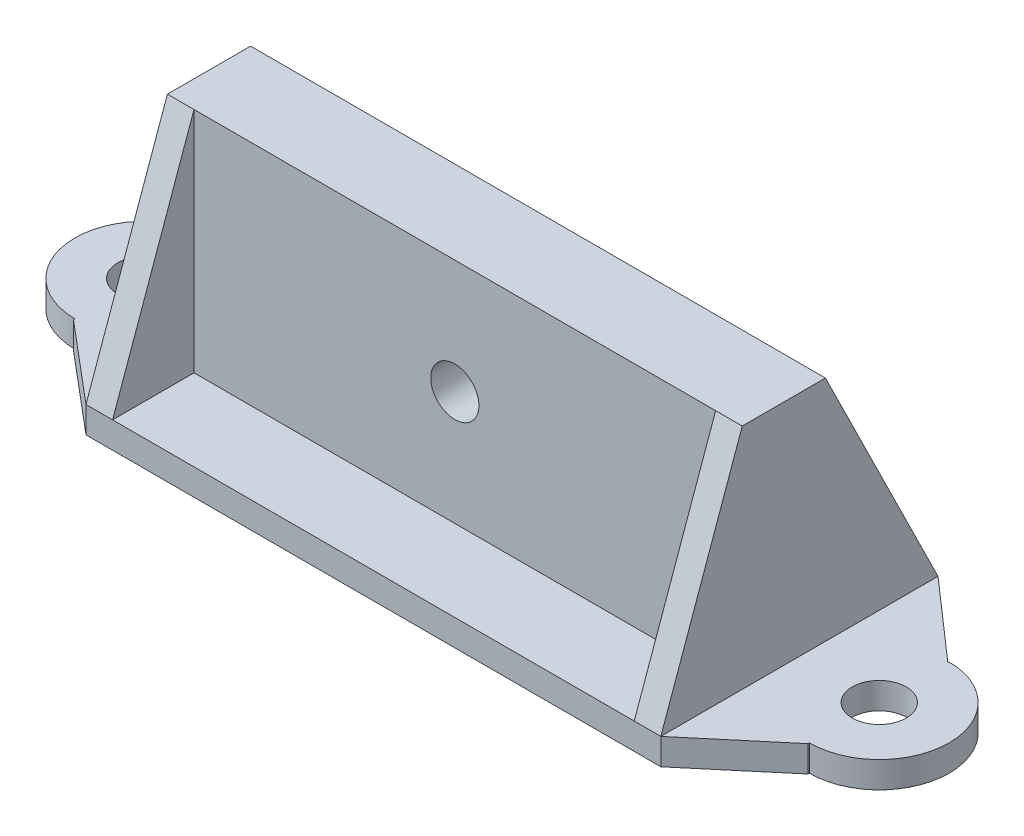
SolidWorks part; units mm, degrees
ref_plane "Alzado" through (0, 0, 0) normal (0, 0, 1) x (1, 0, 0)
ref_plane "Planta" through (0, 0, 0) normal (0, 1, 0) x (1, 0, 0)
ref_plane "Vista lateral" through (0, 0, 0) normal (1, 0, 0) x (0, 0, -1)
sketch "Croquis3" plane through (0, 0, 0) normal (0, 0, 1) x (1, 0, 0)
  line L1 (-37.635, -16.455) -> (37.635, -16.455)
  line L2 (-37.635, -16.455) -> (-37.635, 16.455)
  line L3 (-37.635, 16.455) -> (37.635, 16.455)
  line L4 (37.635, -16.455) -> (37.635, 16.455)
  line L5 (-37.635, -16.455) -> (37.635, 16.455) construction
  line L6 (-37.635, 16.455) -> (37.635, -16.455) construction
  point P0 (0, 0)
  dimension "D1" = 75.27
  dimension "D2" = 32.91
extrude "Saliente-Extruir1" add sketch "Croquis3" along normal blind 3.82
sketch "Croquis4" plane through (37.635, 0, 0) normal (1, 0, 0) x (0, 0, -1)
  line L0 (-3.82, -16.455) -> (0, -16.455)
  line L1 (0, -16.455) -> (0, 16.455)
  line L2 (-3.82, 16.455) -> (0, 16.455) construction
  line L3 (0, -16.455) -> (0, 16.455) construction
  line L4 (0, 16.455) -> (-3.82, 16.455)
  line L5 (-3.82, 16.455) -> (-15.57, -16.455)
  line L6 (-15.57, -16.455) -> (-3.82, -16.455)
  dimension "D1" = 11.75
extrude "Saliente-Extruir2" add sketch "Croquis4" along normal blind 3.84
sketch "Croquis5" plane through (-37.635, 0, 0) normal (-1, 0, 0) x (0, 0, 1)
  line L0 (3.82, -16.455) -> (0, -16.455)
  line L1 (0, -16.455) -> (0, 16.455)
  line L2 (0, 16.455) -> (3.82, 16.455)
  line L3 (3.82, 16.455) -> (15.57, -16.455)
  line L4 (15.57, -16.455) -> (3.82, -16.455)
extrude "Saliente-Extruir3" add sketch "Croquis5" along normal blind 3.84
sketch "Croquis8" plane through (0, -16.455, 0) normal (0, -1, 0) x (-1, 0, 0)
  line L0 (41.475, -15.57) -> (-41.475, -15.57)
  line L1 (-41.475, -15.57) -> (-41.475, 0)
  line L2 (-41.475, 0) -> (41.475, 0)
  line L3 (41.475, 0) -> (41.475, -15.57)
extrude "Saliente-Extruir5" add sketch "Croquis8" along normal blind 3.8
sketch "Croquis9" plane through (0, -20.255, 0) normal (0, -1, 0) x (1, 0, 0)
  line L0 (-41.475, 0) -> (-41.475, -24.43)
  line L5 (41.475, 0) -> (41.475, -24.43)
  line L6 (41.475, -24.43) -> (-41.475, -24.43)
  line L7 (41.475, 15.57) -> (-41.475, 15.57) construction
  line L8 (-41.475, 0) -> (41.475, 0)
  dimension "D1" = 40
extrude "Saliente-Extruir7" add sketch "Croquis9" against normal blind 3.8
sketch "Croquis10" plane through (0, 16.455, 0) normal (0, 1, 0) x (1, 0, 0)
  line L0 (41.475, 24.43) -> (41.475, 0) construction
  line L1 (-41.475, 0) -> (41.475, 0)
  line L2 (-41.475, 0) -> (-41.475, 8.18)
  line L3 (-41.475, 8.18) -> (41.475, 8.18)
  line L4 (41.475, 0) -> (41.475, 8.18)
  line L5 (-37.635, -3.82) -> (37.635, -3.82) construction
  dimension "D1" = 12
extrude "Saliente-Extruir9" add sketch "Croquis10" against normal blind 33.8
sketch "Croquis11" plane through (0, 0, 3.82) normal (0, 0, 1) x (1, 0, 0)
  line L0 (37.635, 16.455) -> (-37.635, 16.455) construction
  line L1 (37.635, -16.455) -> (37.635, 16.455) construction
  circle A0 centre (0, 0) radius 3.475
  point P0 (0, 16.455)
  point P1 (37.635, 0)
  point P4 (0, 0)
  dimension "D1" = 6.95
extrude "Cortar-Extruir3" cut sketch "Croquis11" against normal blind 33.8
sketch "Croquis12" plane through (41.475, 0, 0) normal (1, 0, 0) x (0, 0, -1)
  line L0 (8.18, 16.455) -> (24.43, -16.455)
  line L1 (24.43, -16.455) -> (8.18, -16.455)
  line L2 (8.18, -16.455) -> (8.18, 16.455)
extrude "Saliente-Extruir10" add sketch "Croquis12" against normal blind 3.84
sketch "Croquis14" plane through (-41.475, 0, 0) normal (-1, 0, 0) x (0, 0, 1)
  line L0 (-8.18, 16.455) -> (-8.18, -16.772)
  line L1 (-8.18, -16.772) -> (-24.43, -16.455)
  line L2 (-24.43, -16.455) -> (-8.18, 16.455)
extrude "Saliente-Extruir11" add sketch "Croquis14" against normal blind 3.84
sketch "Croquis15" plane through (0, -20.255, 0) normal (0, -1, 0) x (1, 0, 0)
  line L0 (41.475, 15.57) -> (41.475, -24.43)
  line L1 (52.9958, -14.5227) -> (52.9958, -14.3267)
  line L2 (52.9958, -14.3267) -> (41.475, -24.43)
  line L3 (52.9958, 5.6627) -> (52.9958, 5.8586)
  line L4 (52.9958, 5.8586) -> (41.475, 15.57)
  line L5 (0, 25.6493) -> (0, -36.0289) construction
  line L6 (-52.9958, 5.8586) -> (-41.475, 15.57)
  line L7 (-52.9958, 5.6627) -> (-52.9958, 5.8586)
  line L8 (-52.9958, -14.5227) -> (-52.9958, -14.3267)
  line L9 (-52.9958, -14.3267) -> (-41.475, -24.43)
  line L10 (-41.475, 15.57) -> (-41.475, -24.43)
  circle A0 centre (52.9958, -4.43) radius 3.9
  arc A1 (52.9958, -14.5227) -> (52.9958, 5.6627) centre (52.9958, -4.43) ccw
  circle A2 centre (-52.9958, -4.43) radius 3.9
  arc A3 (-52.9958, -14.5227) -> (-52.9958, 5.6627) centre (-52.9958, -4.43) cw
  point P0 (41.475, 15.57)
  dimension "D1" = 7.8
extrude "Saliente-Extruir12" add sketch "Croquis15" against normal blind 3.8
